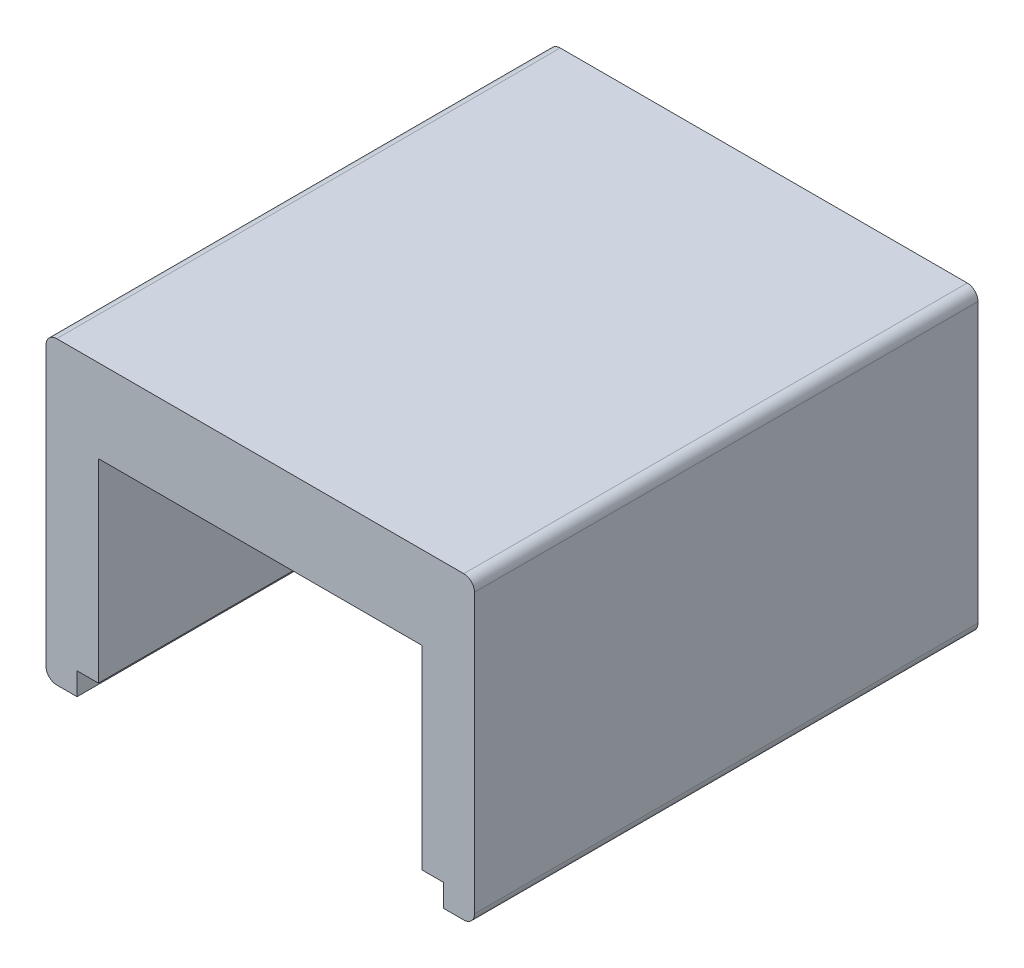
SolidWorks part; units mm, degrees
material "PLA"
ref_plane "Front Plane" through (0, 0, 0) normal (0, 0, 1) x (1, 0, 0)
ref_plane "Top Plane" through (0, 0, 0) normal (0, 1, 0) x (1, 0, 0)
ref_plane "Right Plane" through (0, 0, 0) normal (1, 0, 0) x (0, 0, -1)
sketch "Sketch1" plane through (0, 0, 0) normal (0, 0, 1) x (1, 0, 0)
  line L0 (40, 56) -> (40, 0) construction
  line L1 (0, 0) -> (80, 0)
  line L2 (0, 0) -> (0, 56)
  line L3 (0, 56) -> (80, 56)
  line L4 (80, 0) -> (80, 56)
  line L5 (0, 28) -> (80, 28) construction
  line L7 (9.8, 40.5) -> (70.2, 40.5)
  line L8 (9.8, 40.5) -> (9.8, 10.3)
  line L9 (9.8, 10.3) -> (70.2, 10.3)
  line L10 (70.2, 40.5) -> (70.2, 10.3)
  point P14 (40, 10.3)
  dimension "D1" = 80
  dimension "D2" = 56
  dimension "D3" = 60.4
  dimension "D4" = 30.2
  dimension "D5" = 15.5
extrude "Boss-Extrude1" add sketch "Sketch1" along normal blind 94
sketch "Sketch2" plane through (0, 0, 94) normal (0, 0, 1) x (1, 0, 0)
  line L0 (40, 10.3) -> (40, 0) construction
  line L1 (9.8, 10.3) -> (70.2, 10.3) construction
  line L2 (0, 0) -> (80, 0) construction
  line L4 (9.8, 10.3) -> (70.2, 10.3)
  line L5 (9.8, 10.3) -> (9.8, 4.2)
  line L6 (10, 0) -> (70, 0)
  line L7 (70.2, 10.3) -> (70.2, 4.2)
  line L8 (10, 0) -> (5.8, 0)
  line L10 (9.8, 4.2) -> (5.8, 4.2)
  line L11 (5.8, 0) -> (5.8, 4.2)
  line L12 (70, 0) -> (74.2, 0)
  line L14 (70.2, 4.2) -> (74.2, 4.2)
  line L15 (74.2, 0) -> (74.2, 4.2)
  point P10 (40, 0)
  dimension "D1" = 60
  dimension "D2" = 4
  dimension "D3" = 4.2
  dimension "D4" = 4
  dimension "D5" = 4.2
extrude "Cut-Extrude1" cut sketch "Sketch2" against normal through all
fillet "Fillet1" radius 2 4 edges at (80, 0, 47) (80, 56, 47) (0, 0, 47) (0, 56, 47)
sketch "Sketch3" plane through (80, 0, 0) normal (1, 0, 0) x (0, 0, -1)
  line L0 (-94, 2) -> (-94, 54) construction
  line L1 (-94, 26) -> (0, 26) construction
  line L2 (0, 2) -> (0, 54) construction
  line L3 (0, 0) -> (-94, 0) construction
  line L4 (-94, 56) -> (0, 56) construction
  line L5 (-94, 42) -> (0, 42) construction
  line L6 (0, 10) -> (-94, 10) construction
  line L7 (-94, 42) -> (-94, 10) construction
  line L8 (-94, 10) -> (0, 10) construction
  circle A0 centre (-47, 26) radius 3.2306
  point P16 (-94, 26)
  dimension "D1" = 10
  dimension "D2" = 14
hole_wizard "CBORE for M5 Hex Head Bolt1" positions "Sketch4" profile "Sketch5" counterbore size "M5" standard "ANSI Metric"
sketch "Sketch4" plane through (80, 0, 0) normal (1, 0, 0) x (0, 0, -1)
  point P4 (-70, 25)
sketch "Sketch5" plane through (80, 25, 70) normal (0, 1, 0) x (0, 0, -1)
  line L0 (0, 0) -> (0, 12)
  line L1 (0, 12) -> (2.65, 12)
  line L2 (2.65, 12) -> (2.65, 3.58)
  line L3 (2.65, 3.58) -> (6.12, 3.58)
  line L4 (6.12, 3.58) -> (6.12, 0)
  line L5 (6.12, 0) -> (0, 0)
  line L10 (0, 12) -> (-2.65, 12) construction
  line L11 (0, -6.35) -> (0, 107.95) construction
  dimension "Hole Dia." = 5.3
  dimension "Hole Depth" = 12
  dimension "C'Bore Dia." = 12.24
  dimension "C'Bore Depth" = 3.58
  dimension "Drill Angle" = 180
